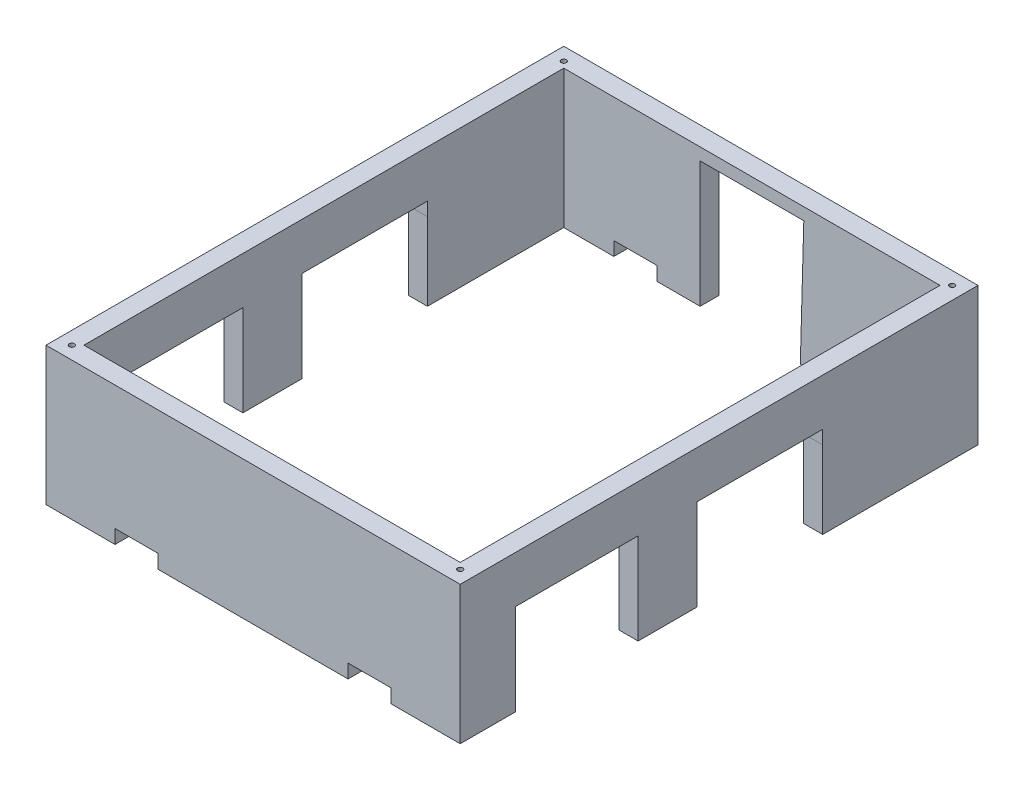
SolidWorks part; units mm, degrees
ref_plane "Front Plane" through (0, 0, 0) normal (0, 0, 1) x (1, 0, 0)
ref_plane "Top Plane" through (0, 0, 0) normal (0, 1, 0) x (1, 0, 0)
ref_plane "Right Plane" through (0, 0, 0) normal (1, 0, 0) x (0, 0, -1)
sketch "Sketch1" plane through (0, 0, 0) normal (0, 1, 0) x (1, 0, 0)
  line L1 (120, -150) -> (-120, -150)
  line L2 (120, -150) -> (120, 150)
  line L3 (120, 150) -> (-120, 150)
  line L4 (-120, -150) -> (-120, 150)
  line L5 (120, -150) -> (-120, 150) construction
  line L6 (120, 150) -> (-120, -150) construction
  point P0 (0, 0)
extrude "Boss-Extrude1" add sketch "Sketch1" along normal blind 80
shell "Shell1" thickness 11
sketch "Sketch4" plane through (0, 80, 0) normal (0, 1, 0) x (1, 0, 0)
  circle A0 centre (-112.5, 142.5) radius 1.5
extrude "Cut-Extrude2" cut sketch "Sketch4" against normal through all from surface at 0 starting at face at (0, 80, 0)
mirror "Mirror1" about plane through (0, 0, 0) normal (1, 0, 0) of "Cut-Extrude2"
mirror "Mirror2" about plane through (0, 0, 0) normal (0, 0, 1) of "Mirror1", "Cut-Extrude2"
sketch "Sketch16" plane through (0, 0, 150) normal (0, 0, 1) x (1, 0, 0)
  line L0 (-80, 0) -> (-55, 0)
  line L1 (-120, 0) -> (120, 0) construction
  line L2 (-80, 0) -> (-80, 8)
  line L3 (-80, 8) -> (-55, 8)
  line L4 (-55, 8) -> (-55, 0)
extrude "Cut-Extrude9" cut sketch "Sketch16" against normal through all
mirror "Mirror3" about plane through (0, 0, 0) normal (1, 0, 0) of "Cut-Extrude9"
sketch "Sketch18" plane through (120, 0, 0) normal (1, 0, 0) x (0, 0, -1)
  line L0 (150, 0) -> (60, 0)
  line L1 (-150, 0) -> (150, 0) construction
  line L2 (150, 80) -> (150, 0) construction
  line L3 (60, 0) -> (60, 45)
  line L4 (60, 45) -> (-12.7, 45)
  line L5 (-12.7, 45) -> (-12.7, 0)
  line L6 (-12.7, 0) -> (60, 0)
  line L7 (-150, 0) -> (-118.03, 0)
  line L8 (-118.03, 0) -> (-118.03, 45)
  line L9 (-118.03, 45) -> (-46.93, 45)
  line L10 (-46.93, 45) -> (-46.93, 0)
  line L11 (-46.93, 0) -> (-118.03, 0)
  line M6 (-150, 0) -> (150, 0)
extrude "Cut-Extrude10" cut sketch "Sketch18" against normal through all contours L10 L9 L8 M6 | L4 L5 L3 M6
sketch "Sketch19" plane through (120, 0, 0) normal (1, 0, 0) x (0, 0, -1)
  line L1 (-118.03, 45) -> (-46.93, 45)
  line L2 (-118.03, 45) -> (-118.03, 52.8109)
  line L3 (-118.03, 52.8109) -> (-46.93, 52.8109)
  line L4 (-46.93, 45) -> (-46.93, 52.8109)
  line L5 (-12.7, 45) -> (59.9742, 45)
  line L6 (-12.7, 45) -> (-12.7, 52.8109)
  line L7 (-12.7, 52.8109) -> (59.9742, 52.8109)
  line L8 (59.9742, 45) -> (59.9742, 52.8109)
extrude "Cut-Extrude11" cut sketch "Sketch19" against normal through all
sketch "Sketch22" plane through (0, 0, -150) normal (0, 0, -1) x (-1, 0, 0)
  line L0 (-28.0415, 0) -> (30, 0)
  line L1 (-28.0415, 0) -> (-30.0717, 72.9718)
  line L12 (-55, 0) -> (55, 0) construction
  line L13 (30, 72.9718) -> (30, 0)
  line L14 (-30.0717, 72.9718) -> (30, 72.9718)
  point P9 (0, 32.7151)
extrude "Cut-Extrude12" cut sketch "Sketch22" against normal blind 15
